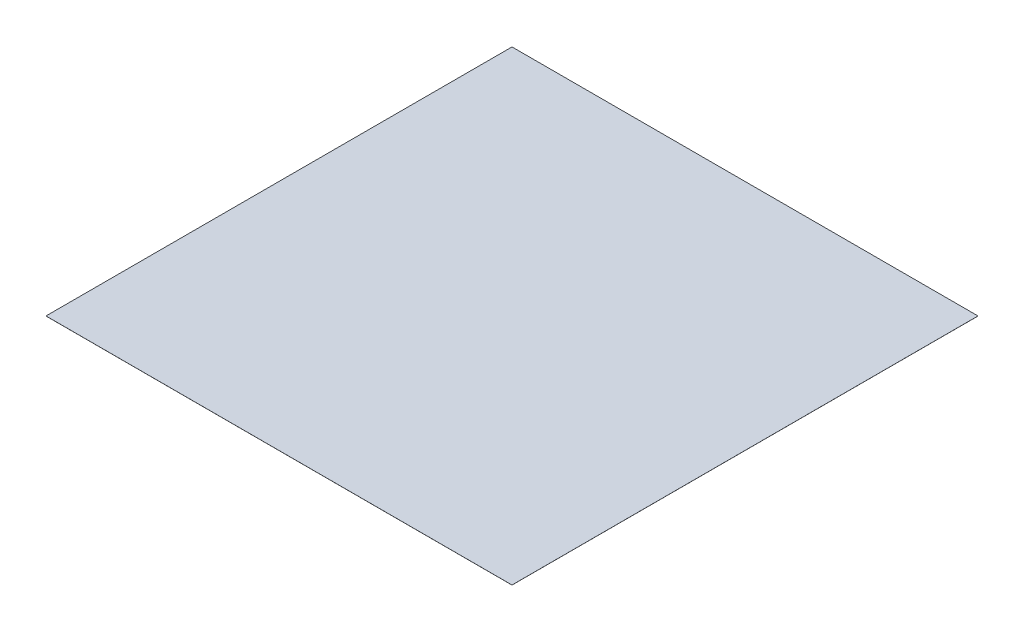
SolidWorks part; units mm, degrees
ref_plane "Front Plane" through (0, 0, 0) normal (0, 0, 1) x (1, 0, 0)
ref_plane "Top Plane" through (0, 0, 0) normal (0, 1, 0) x (1, 0, 0)
ref_plane "Right Plane" through (0, 0, 0) normal (1, 0, 0) x (0, 0, -1)
sketch "Sketch1" plane through (0, 0, 0) normal (0, 1, 0) x (1, 0, 0)
  line L1 (-3000, -3000) -> (3000, -3000)
  line L2 (-3000, -3000) -> (-3000, 3000)
  line L3 (-3000, 3000) -> (3000, 3000)
  line L4 (3000, -3000) -> (3000, 3000)
  line L5 (-3000, -3000) -> (3000, 3000) construction
  line L6 (-3000, 3000) -> (3000, -3000) construction
  point P0 (0, 0)
  dimension "D1" = 6000
  dimension "D2" = 6000
extrude "Boss-Extrude1" add sketch "Sketch1" along normal blind 1
